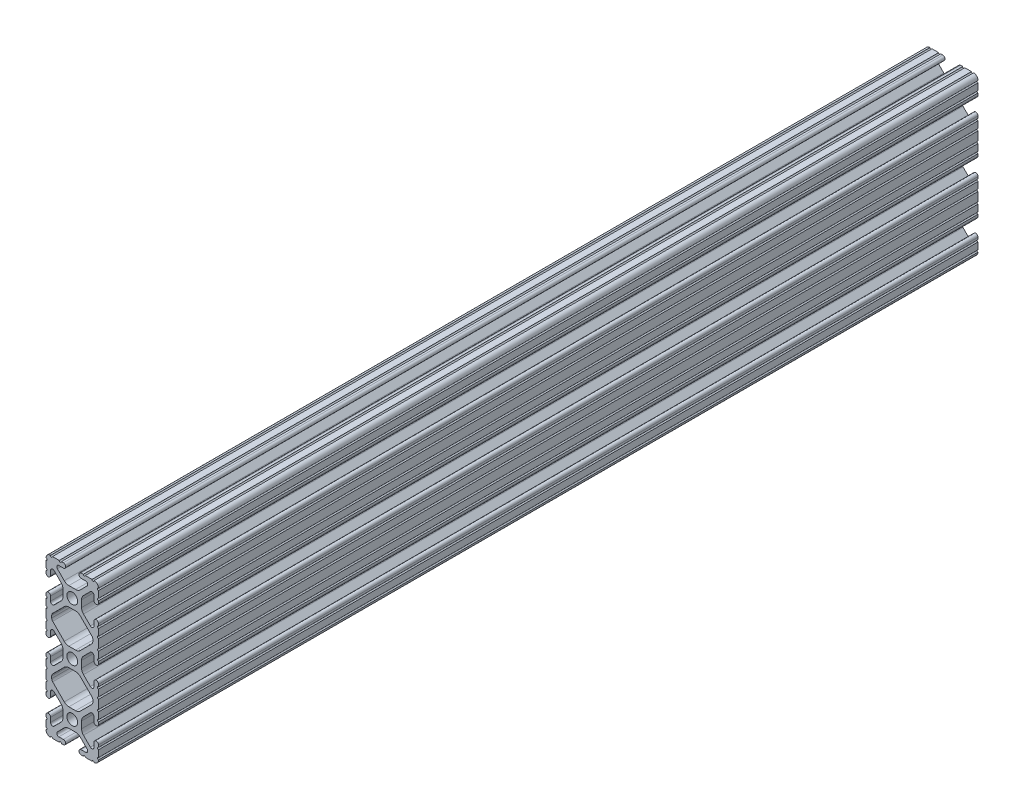
SolidWorks part; units mm, degrees
ref_plane "Front Plane" through (0, 0, 0) normal (0, 0, 1) x (1, 0, 0)
ref_plane "Top Plane" through (0, 0, 0) normal (0, 1, 0) x (1, 0, 0)
ref_plane "Right Plane" through (0, 0, 0) normal (1, 0, 0) x (0, 0, -1)
sketch "Sketch1" plane through (0, 0, 0) normal (0, 0, 1) x (1, 0, 0)
  line L0 (-9.9314, 12.1463) -> (-9.9314, 13.2537)
  line L1 (-9.4702, 14.3673) -> (-3.8759, 19.9616)
  line L2 (-1.6308, 20.8915) -> (1.6308, 20.8915)
  line L3 (3.8759, 19.9616) -> (9.4702, 14.3673)
  line L4 (9.9314, 13.2537) -> (9.9314, 12.1463)
  line L5 (9.4702, 11.0327) -> (3.8759, 5.4384)
  line L6 (1.6308, 4.5085) -> (-1.6308, 4.5085)
  line L7 (-3.8759, 5.4384) -> (-9.4702, 11.0327)
  line L8 (-9.9314, -13.2537) -> (-9.9314, -12.1463)
  line L9 (-9.4702, -11.0327) -> (-3.8759, -5.4384)
  line L10 (-1.6308, -4.5085) -> (1.6308, -4.5085)
  line L11 (3.8759, -5.4384) -> (9.4702, -11.0327)
  line L12 (9.9314, -12.1463) -> (9.9314, -13.2537)
  line L13 (9.4702, -14.3673) -> (3.8759, -19.9616)
  line L14 (1.6308, -20.8915) -> (-1.6308, -20.8915)
  line L15 (-3.8759, -19.9616) -> (-9.4702, -14.3673)
  line L16 (-6.3246, 38.1) -> (-9.5504, 38.1)
  line L17 (-12.7, 34.9504) -> (-12.7, 31.7246)
  line L18 (-12.7, 30.7086) -> (-12.7, 29.7023)
  line L19 (-10.4902, 29.7023) -> (-10.4902, 31.8748)
  line L20 (-8.7558, 32.5932) -> (-5.4384, 29.2759)
  line L21 (-4.5085, 27.0308) -> (-4.5085, 23.7692)
  line L22 (-5.4384, 21.5241) -> (-8.7558, 18.2068)
  line L23 (-10.4902, 18.9252) -> (-10.4902, 21.0977)
  line L24 (-12.7, 21.0977) -> (-12.7, 20.0914)
  line L25 (-12.7, 19.0754) -> (-12.7, 15.8496)
  line L26 (-12.7, 14.8336) -> (-12.7, 10.5664)
  line L27 (-12.7, 9.5504) -> (-12.7, 6.3246)
  line L28 (-12.7, 5.3086) -> (-12.7, 4.3023)
  line L29 (-10.4902, 4.3023) -> (-10.4902, 6.4748)
  line L30 (-8.7558, 7.1932) -> (-5.4384, 3.8759)
  line L31 (-4.5085, 1.6308) -> (-4.5085, -1.6308)
  line L32 (-5.4384, -3.8759) -> (-8.7558, -7.1932)
  line L33 (-10.4902, -6.4748) -> (-10.4902, -4.3023)
  line L34 (-12.7, -4.3023) -> (-12.7, -5.3086)
  line L35 (-12.7, -6.3246) -> (-12.7, -9.5504)
  line L36 (-12.7, -10.5664) -> (-12.7, -14.8336)
  line L37 (-12.7, -15.8496) -> (-12.7, -19.0754)
  line L38 (-12.7, -20.0914) -> (-12.7, -21.0977)
  line L39 (-10.4902, -21.0977) -> (-10.4902, -18.9252)
  line L40 (-8.7558, -18.2068) -> (-5.4384, -21.5241)
  line L41 (-4.5085, -23.7692) -> (-4.5085, -27.0308)
  line L42 (-5.4384, -29.2759) -> (-8.7558, -32.5932)
  line L43 (-10.4902, -31.8748) -> (-10.4902, -29.7023)
  line L44 (-12.7, -29.7023) -> (-12.7, -30.7086)
  line L45 (-12.7, -31.7246) -> (-12.7, -34.9504)
  line L46 (-9.5504, -38.1) -> (-6.3246, -38.1)
  line L47 (-5.3086, -38.1) -> (-4.3023, -38.1)
  line L48 (-4.3023, -35.8902) -> (-6.4748, -35.8902)
  line L49 (-7.1932, -34.1558) -> (-3.8759, -30.8384)
  line L50 (-1.6308, -29.9085) -> (1.6308, -29.9085)
  line L51 (3.8759, -30.8384) -> (7.1932, -34.1558)
  line L52 (6.4748, -35.8902) -> (4.3023, -35.8902)
  line L53 (4.3023, -38.1) -> (5.3086, -38.1)
  line L54 (6.3246, -38.1) -> (9.5504, -38.1)
  line L55 (12.7, -34.9504) -> (12.7, -31.7246)
  line L56 (12.7, -30.7086) -> (12.7, -29.7023)
  line L57 (10.4902, -29.7023) -> (10.4902, -31.8748)
  line L58 (8.7558, -32.5932) -> (5.4384, -29.2759)
  line L59 (4.5085, -27.0308) -> (4.5085, -23.7692)
  line L60 (5.4384, -21.5241) -> (8.7558, -18.2068)
  line L61 (10.4902, -18.9252) -> (10.4902, -21.0977)
  line L62 (12.7, -21.0977) -> (12.7, -20.0914)
  line L63 (12.7, -19.0754) -> (12.7, -15.8496)
  line L64 (12.7, -14.8336) -> (12.7, -10.5664)
  line L65 (12.7, -9.5504) -> (12.7, -6.3246)
  line L66 (12.7, -5.3086) -> (12.7, -4.3023)
  line L67 (10.4902, -4.3023) -> (10.4902, -6.4748)
  line L68 (8.7558, -7.1932) -> (5.4384, -3.8759)
  line L69 (4.5085, -1.6308) -> (4.5085, 1.6308)
  line L70 (5.4384, 3.8759) -> (8.7558, 7.1932)
  line L71 (10.4902, 6.4748) -> (10.4902, 4.3023)
  line L72 (12.7, 4.3023) -> (12.7, 5.3086)
  line L73 (12.7, 6.3246) -> (12.7, 9.5504)
  line L74 (12.7, 10.5664) -> (12.7, 14.8336)
  line L75 (12.7, 15.8496) -> (12.7, 19.0754)
  line L76 (12.7, 20.0914) -> (12.7, 21.0977)
  line L77 (10.4902, 21.0977) -> (10.4902, 18.9252)
  line L78 (8.7558, 18.2068) -> (5.4384, 21.5241)
  line L79 (4.5085, 23.7692) -> (4.5085, 27.0308)
  line L80 (5.4384, 29.2759) -> (8.7558, 32.5932)
  line L81 (10.4902, 31.8748) -> (10.4902, 29.7023)
  line L82 (12.7, 29.7023) -> (12.7, 30.7086)
  line L83 (12.7, 31.7246) -> (12.7, 34.9504)
  line L84 (9.5504, 38.1) -> (6.3246, 38.1)
  line L85 (5.3086, 38.1) -> (4.3023, 38.1)
  line L86 (4.3023, 35.8902) -> (6.4748, 35.8902)
  line L87 (7.1932, 34.1558) -> (3.8759, 30.8384)
  line L88 (1.6308, 29.9085) -> (-1.6308, 29.9085)
  line L89 (-3.8759, 30.8384) -> (-7.1932, 34.1558)
  line L90 (-6.4748, 35.8902) -> (-4.3023, 35.8902)
  line L91 (-4.3023, 38.1) -> (-5.3086, 38.1)
  circle A0 centre (0, 25.4) radius 2.6035
  arc A1 (-9.9314, 13.2537) -> (-9.4702, 14.3673) centre (-8.3566, 13.2537) cw
  arc A2 (-3.8759, 19.9616) -> (-1.6308, 20.8915) centre (-1.6308, 17.7165) cw
  arc A3 (1.6308, 20.8915) -> (3.8759, 19.9616) centre (1.6308, 17.7165) cw
  arc A4 (9.4702, 14.3673) -> (9.9314, 13.2537) centre (8.3566, 13.2537) cw
  arc A5 (9.9314, 12.1463) -> (9.4702, 11.0327) centre (8.3566, 12.1463) cw
  arc A6 (3.8759, 5.4384) -> (1.6308, 4.5085) centre (1.6308, 7.6835) cw
  arc A7 (-1.6308, 4.5085) -> (-3.8759, 5.4384) centre (-1.6308, 7.6835) cw
  arc A8 (-9.4702, 11.0327) -> (-9.9314, 12.1463) centre (-8.3566, 12.1463) cw
  arc A9 (-9.9314, -12.1463) -> (-9.4702, -11.0327) centre (-8.3566, -12.1463) cw
  arc A10 (-3.8759, -5.4384) -> (-1.6308, -4.5085) centre (-1.6308, -7.6835) cw
  arc A11 (1.6308, -4.5085) -> (3.8759, -5.4384) centre (1.6308, -7.6835) cw
  arc A12 (9.4702, -11.0327) -> (9.9314, -12.1463) centre (8.3566, -12.1463) cw
  arc A13 (9.9314, -13.2537) -> (9.4702, -14.3673) centre (8.3566, -13.2537) cw
  arc A14 (3.8759, -19.9616) -> (1.6308, -20.8915) centre (1.6308, -17.7165) cw
  arc A15 (-1.6308, -20.8915) -> (-3.8759, -19.9616) centre (-1.6308, -17.7165) cw
  arc A16 (-9.4702, -14.3673) -> (-9.9314, -13.2537) centre (-8.3566, -13.2537) cw
  circle A17 centre (0, -25.4) radius 2.6035
  circle A18 centre (0, 0) radius 2.6035
  arc A19 (-5.3086, 38.1) -> (-6.3246, 38.1) centre (-5.8166, 38.1) cw
  arc A20 (-9.5504, 38.1) -> (-10.5664, 38.1) centre (-10.0584, 38.1) cw
  arc A21 (-10.5664, 38.1) -> (-12.7, 35.9664) centre (-10.592, 35.992) ccw
  arc A22 (-12.7, 35.9664) -> (-12.7, 34.9504) centre (-12.7, 35.4584) cw
  arc A23 (-12.7, 31.7246) -> (-12.7, 30.7086) centre (-12.7, 31.2166) cw
  arc A24 (-12.7, 29.7023) -> (-10.4902, 29.7023) centre (-11.5951, 29.7023) ccw
  arc A25 (-10.4902, 31.8748) -> (-8.7558, 32.5932) centre (-9.4742, 31.8748) cw
  arc A26 (-5.4384, 29.2759) -> (-4.5085, 27.0308) centre (-7.6835, 27.0308) cw
  arc A27 (-4.5085, 23.7692) -> (-5.4384, 21.5241) centre (-7.6835, 23.7692) cw
  arc A28 (-8.7558, 18.2068) -> (-10.4902, 18.9252) centre (-9.4742, 18.9252) cw
  arc A29 (-10.4902, 21.0977) -> (-12.7, 21.0977) centre (-11.5951, 21.0977) ccw
  arc A30 (-12.7, 20.0914) -> (-12.7, 19.0754) centre (-12.7, 19.5834) cw
  arc A31 (-12.7, 15.8496) -> (-12.7, 14.8336) centre (-12.7, 15.3416) cw
  arc A32 (-12.7, 10.5664) -> (-12.7, 9.5504) centre (-12.7, 10.0584) cw
  arc A33 (-12.7, 6.3246) -> (-12.7, 5.3086) centre (-12.7, 5.8166) cw
  arc A34 (-12.7, 4.3023) -> (-10.4902, 4.3023) centre (-11.5951, 4.3023) ccw
  arc A35 (-10.4902, 6.4748) -> (-8.7558, 7.1932) centre (-9.4742, 6.4748) cw
  arc A36 (-5.4384, 3.8759) -> (-4.5085, 1.6308) centre (-7.6835, 1.6308) cw
  arc A37 (-4.5085, -1.6308) -> (-5.4384, -3.8759) centre (-7.6835, -1.6308) cw
  arc A38 (-8.7558, -7.1932) -> (-10.4902, -6.4748) centre (-9.4742, -6.4748) cw
  arc A39 (-10.4902, -4.3023) -> (-12.7, -4.3023) centre (-11.5951, -4.3023) ccw
  arc A40 (-12.7, -5.3086) -> (-12.7, -6.3246) centre (-12.7, -5.8166) cw
  arc A41 (-12.7, -9.5504) -> (-12.7, -10.5664) centre (-12.7, -10.0584) cw
  arc A42 (-12.7, -14.8336) -> (-12.7, -15.8496) centre (-12.7, -15.3416) cw
  arc A43 (-12.7, -19.0754) -> (-12.7, -20.0914) centre (-12.7, -19.5834) cw
  arc A44 (-12.7, -21.0977) -> (-10.4902, -21.0977) centre (-11.5951, -21.0977) ccw
  arc A45 (-10.4902, -18.9252) -> (-8.7558, -18.2068) centre (-9.4742, -18.9252) cw
  arc A46 (-5.4384, -21.5241) -> (-4.5085, -23.7692) centre (-7.6835, -23.7692) cw
  arc A47 (-4.5085, -27.0308) -> (-5.4384, -29.2759) centre (-7.6835, -27.0308) cw
  arc A48 (-8.7558, -32.5932) -> (-10.4902, -31.8748) centre (-9.4742, -31.8748) cw
  arc A49 (-10.4902, -29.7023) -> (-12.7, -29.7023) centre (-11.5951, -29.7023) ccw
  arc A50 (-12.7, -30.7086) -> (-12.7, -31.7246) centre (-12.7, -31.2166) cw
  arc A51 (-12.7, -34.9504) -> (-12.7, -35.9664) centre (-12.7, -35.4584) cw
  arc A52 (-12.7, -35.9664) -> (-10.5664, -38.1) centre (-10.592, -35.992) ccw
  arc A53 (-10.5664, -38.1) -> (-9.5504, -38.1) centre (-10.0584, -38.1) cw
  arc A54 (-6.3246, -38.1) -> (-5.3086, -38.1) centre (-5.8166, -38.1) cw
  arc A55 (-4.3023, -38.1) -> (-4.3023, -35.8902) centre (-4.3023, -36.9951) ccw
  arc A56 (-6.4748, -35.8902) -> (-7.1932, -34.1558) centre (-6.4748, -34.8742) cw
  arc A57 (-3.8759, -30.8384) -> (-1.6308, -29.9085) centre (-1.6308, -33.0835) cw
  arc A58 (1.6308, -29.9085) -> (3.8759, -30.8384) centre (1.6308, -33.0835) cw
  arc A59 (7.1932, -34.1558) -> (6.4748, -35.8902) centre (6.4748, -34.8742) cw
  arc A60 (4.3023, -35.8902) -> (4.3023, -38.1) centre (4.3023, -36.9951) ccw
  arc A61 (5.3086, -38.1) -> (6.3246, -38.1) centre (5.8166, -38.1) cw
  arc A62 (9.5504, -38.1) -> (10.5664, -38.1) centre (10.0584, -38.1) cw
  arc A63 (10.5664, -38.1) -> (12.7, -35.9664) centre (10.592, -35.992) ccw
  arc A64 (12.7, -35.9664) -> (12.7, -34.9504) centre (12.7, -35.4584) cw
  arc A65 (12.7, -31.7246) -> (12.7, -30.7086) centre (12.7, -31.2166) cw
  arc A66 (12.7, -29.7023) -> (10.4902, -29.7023) centre (11.5951, -29.7023) ccw
  arc A67 (10.4902, -31.8748) -> (8.7558, -32.5932) centre (9.4742, -31.8748) cw
  arc A68 (5.4384, -29.2759) -> (4.5085, -27.0308) centre (7.6835, -27.0308) cw
  arc A69 (4.5085, -23.7692) -> (5.4384, -21.5241) centre (7.6835, -23.7692) cw
  arc A70 (8.7558, -18.2068) -> (10.4902, -18.9252) centre (9.4742, -18.9252) cw
  arc A71 (10.4902, -21.0977) -> (12.7, -21.0977) centre (11.5951, -21.0977) ccw
  arc A72 (12.7, -20.0914) -> (12.7, -19.0754) centre (12.7, -19.5834) cw
  arc A73 (12.7, -15.8496) -> (12.7, -14.8336) centre (12.7, -15.3416) cw
  arc A74 (12.7, -10.5664) -> (12.7, -9.5504) centre (12.7, -10.0584) cw
  arc A75 (12.7, -6.3246) -> (12.7, -5.3086) centre (12.7, -5.8166) cw
  arc A76 (12.7, -4.3023) -> (10.4902, -4.3023) centre (11.5951, -4.3023) ccw
  arc A77 (10.4902, -6.4748) -> (8.7558, -7.1932) centre (9.4742, -6.4748) cw
  arc A78 (5.4384, -3.8759) -> (4.5085, -1.6308) centre (7.6835, -1.6308) cw
  arc A79 (4.5085, 1.6308) -> (5.4384, 3.8759) centre (7.6835, 1.6308) cw
  arc A80 (8.7558, 7.1932) -> (10.4902, 6.4748) centre (9.4742, 6.4748) cw
  arc A81 (10.4902, 4.3023) -> (12.7, 4.3023) centre (11.5951, 4.3023) ccw
  arc A82 (12.7, 5.3086) -> (12.7, 6.3246) centre (12.7, 5.8166) cw
  arc A83 (12.7, 9.5504) -> (12.7, 10.5664) centre (12.7, 10.0584) cw
  arc A84 (12.7, 14.8336) -> (12.7, 15.8496) centre (12.7, 15.3416) cw
  arc A85 (12.7, 19.0754) -> (12.7, 20.0914) centre (12.7, 19.5834) cw
  arc A86 (12.7, 21.0977) -> (10.4902, 21.0977) centre (11.5951, 21.0977) ccw
  arc A87 (10.4902, 18.9252) -> (8.7558, 18.2068) centre (9.4742, 18.9252) cw
  arc A88 (5.4384, 21.5241) -> (4.5085, 23.7692) centre (7.6835, 23.7692) cw
  arc A89 (4.5085, 27.0308) -> (5.4384, 29.2759) centre (7.6835, 27.0308) cw
  arc A90 (8.7558, 32.5932) -> (10.4902, 31.8748) centre (9.4742, 31.8748) cw
  arc A91 (10.4902, 29.7023) -> (12.7, 29.7023) centre (11.5951, 29.7023) ccw
  arc A92 (12.7, 30.7086) -> (12.7, 31.7246) centre (12.7, 31.2166) cw
  arc A93 (12.7, 34.9504) -> (12.7, 35.9664) centre (12.7, 35.4584) cw
  arc A94 (12.7, 35.9664) -> (10.5664, 38.1) centre (10.592, 35.992) ccw
  arc A95 (10.5664, 38.1) -> (9.5504, 38.1) centre (10.0584, 38.1) cw
  arc A96 (6.3246, 38.1) -> (5.3086, 38.1) centre (5.8166, 38.1) cw
  arc A97 (4.3023, 38.1) -> (4.3023, 35.8902) centre (4.3023, 36.9951) ccw
  arc A98 (6.4748, 35.8902) -> (7.1932, 34.1558) centre (6.4748, 34.8742) cw
  arc A99 (3.8759, 30.8384) -> (1.6308, 29.9085) centre (1.6308, 33.0835) cw
  arc A100 (-1.6308, 29.9085) -> (-3.8759, 30.8384) centre (-1.6308, 33.0835) cw
  arc A101 (-7.1932, 34.1558) -> (-6.4748, 35.8902) centre (-6.4748, 34.8742) cw
  arc A102 (-4.3023, 35.8902) -> (-4.3023, 38.1) centre (-4.3023, 36.9951) ccw
extrude "Boss-Extrude1" add sketch "Sketch1" against normal blind 425.45
